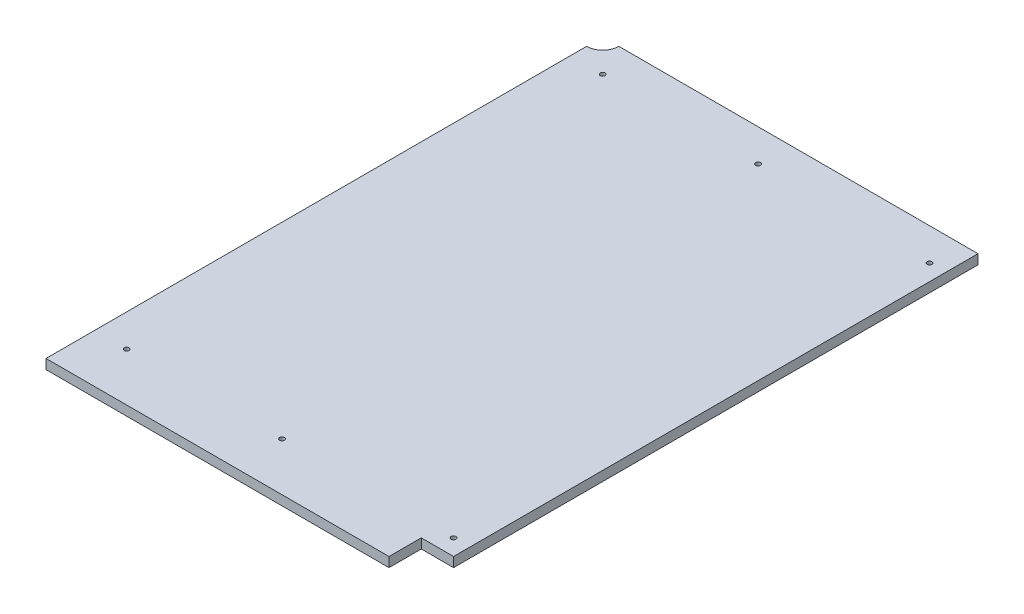
SolidWorks part; units mm, degrees
ref_plane "前视基准面" through (0, 0, 0) normal (0, 0, 1) x (1, 0, 0)
ref_plane "上视基准面" through (0, 0, 0) normal (0, 1, 0) x (1, 0, 0)
ref_plane "右视基准面" through (0, 0, 0) normal (1, 0, 0) x (0, 0, -1)
sketch "草图1" plane through (0, 0, 0) normal (0, 1, 0) x (1, 0, 0)
  line L0 (-112.725, 93.5) -> (119.825, 93.5) construction
  line L1 (-102.725, 113.5) -> (119.825, 113.5)
  line L2 (-112.725, 103.5) -> (-112.725, -221.5)
  line L3 (-102.725, -231.5) -> (99.825, -231.5)
  line L4 (119.825, 113.5) -> (119.825, -211.5)
  line L5 (-112.725, -201.5) -> (119.825, -201.5) construction
  line L8 (99.825, -231.5) -> (99.825, -211.5)
  line L9 (99.825, -211.5) -> (119.825, -211.5)
  line L10 (-112.725, -221.5) -> (-112.725, -231.5)
  line L11 (-112.725, -231.5) -> (-102.725, -231.5)
  circle A0 centre (-92.725, 93.5) radius 1.5
  circle A1 centre (109.825, 93.5) radius 1.5
  circle A2 centre (3.55, 93.5) radius 1.5
  circle A3 centre (-92.725, -201.5) radius 1.5
  circle A4 centre (3.55, -201.5) radius 1.5
  circle A5 centre (109.825, -201.5) radius 1.5
  arc A7 (-112.725, 103.5) -> (-102.725, 113.5) centre (-112.725, 113.5) ccw
  dimension "D7" = 3
  dimension "D9" = 3
  dimension "D11" = 3
  dimension "D12" = 3
  dimension "D13" = 3
  dimension "D14" = 3
  dimension "D19" = 20
  dimension "D2" = 345
  dimension "D3" = 112.725
  dimension "D4" = 113.5
  dimension "D5" = 20
  dimension "D6" = 30
  dimension "D8" = 20
  dimension "D10" = 10
  dimension "D15" = 232.55
  dimension "D16" = 20
  dimension "D17" = 10
  dimension "D18" = 20
extrude "凸台-拉伸1" add sketch "草图1" along normal blind 6
